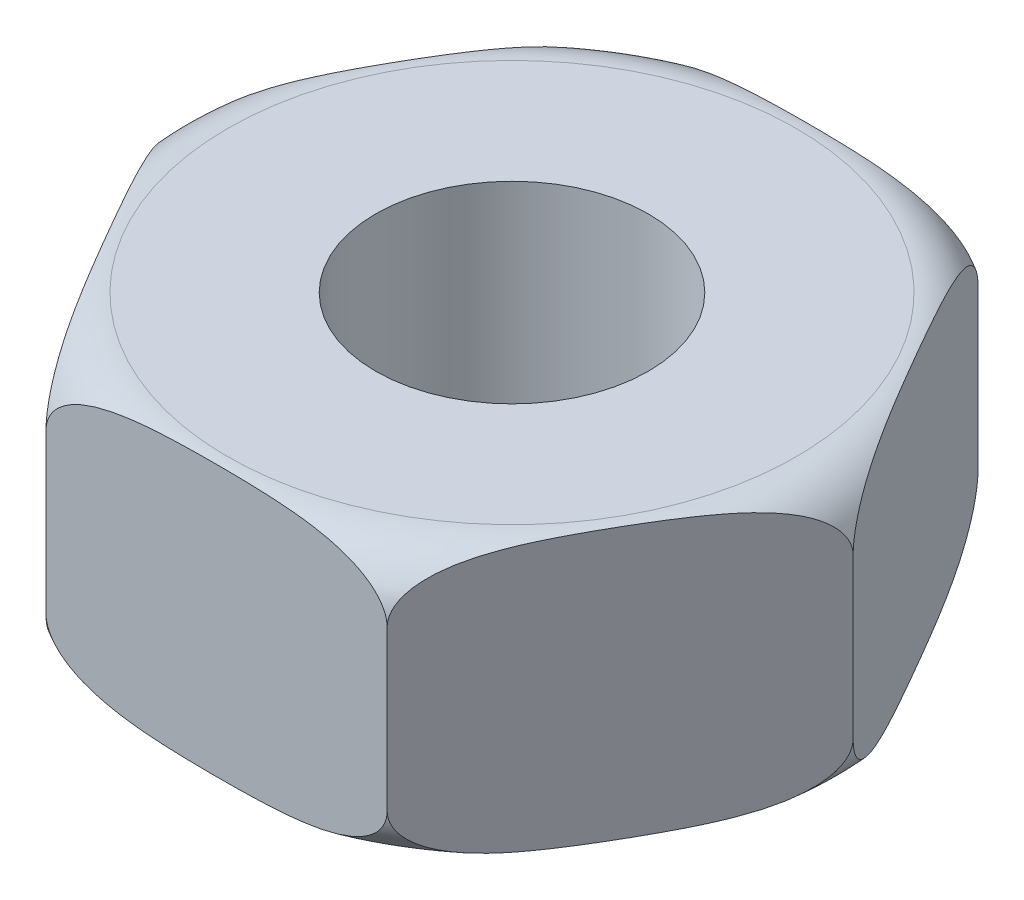
SolidWorks part; units mm, degrees
ref_plane "Front Plane" through (0, 0, 0) normal (0, 0, 1) x (1, 0, 0)
ref_plane "Top Plane" through (0, 0, 0) normal (0, 1, 0) x (1, 0, 0)
ref_plane "Right Plane" through (0, 0, 0) normal (1, 0, 0) x (0, 0, -1)
sketch "Sketch1" plane through (0, 0, 0) normal (0, 1, 0) x (1, 0, 0)
  line L0 (-15.0111, 0) -> (15.0111, 0) construction
  line L1 (7.5056, 13) -> (-7.5056, 13)
  line L2 (-7.5056, 13) -> (-15.0111, 0)
  line L3 (-15.0111, 0) -> (-7.5056, -13)
  line L4 (-7.5056, -13) -> (7.5056, -13)
  line L5 (7.5056, -13) -> (15.0111, 0)
  line L6 (15.0111, 0) -> (7.5056, 13)
  circle A0 centre (0, 0) radius 13 construction
  dimension "D1" = 26
extrude "Boss-Extrude1" add sketch "Sketch1" along normal blind 12
hole_wizard "Ø12.0mm Dowel Hole1" positions "Sketch3" profile "Sketch2" hole size "Ø12.0" standard "ANSI Metric" end condition through all
sketch "Sketch3" plane through (0, 0, 0) normal (0, -1, 0) x (-1, 0, 0)
  point P0 (0, 0)
sketch "Sketch2" plane through (0, 0, 0) normal (1, 0, 0) x (0, 0, -1)
  line L0 (0, 0) -> (0, 12)
  line L1 (0, 12) -> (6, 12)
  line L2 (6, 12) -> (6, 0)
  line L5 (6, 0) -> (0, 0)
  line L11 (0, -6.35) -> (0, 107.95) construction
  dimension "Thru Hole Dia." = 12
  dimension "Thru Hole Depth" = 12
sketch "Sketch4" plane through (0, 0, 0) normal (0, 0, 1) x (1, 0, 0)
  line L0 (0, 14.4064) -> (0, -3.2931) construction
  line L2 (19.3814, -4.5325) -> (19.3814, 2.5)
  line L4 (15.0111, 12) -> (15.0111, 0) construction
  line L6 (-15.0111, 6) -> (15.0111, 6) construction
  line L7 (-15.0111, 12) -> (-15.0111, 0) construction
  line L17 (12.5111, 12) -> (12.5111, 16.5325)
  line L18 (7.5056, 12) -> (15.0111, 12) construction
  line L19 (12.5111, 16.5325) -> (19.3814, 16.5325)
  line L20 (19.3814, 16.5325) -> (19.3814, 9.5)
  line L21 (19.3814, 9.5) -> (15.0111, 9.5)
  line L22 (12.5111, 12) -> (12.5111, 9.5) construction
  line L23 (12.5111, 9.5) -> (15.0111, 9.5) construction
  line L24 (12.5111, -4.5325) -> (19.3814, -4.5325)
  line L25 (12.5111, 0) -> (12.5111, -4.5325)
  line L26 (19.3814, 2.5) -> (15.0111, 2.5)
  arc A0 (12.5111, 12) -> (15.0111, 9.5) centre (12.5111, 9.5) cw
  arc A1 (12.5111, 0) -> (15.0111, 2.5) centre (12.5111, 2.5) ccw
  point P24 (-26.8849, 8.585)
  dimension "D1" = 2.5
revolve "Cut-Revolve2" cut sketch "Sketch4" angle 360 about L0
ref_plane "Plane1" through (0, 6, 0) normal (0, -1, 0) x (-1, 0, 0)
mirror "Mirror1" about plane through (0, 6, 0) normal (0, -1, 0) of "Cut-Revolve2"
